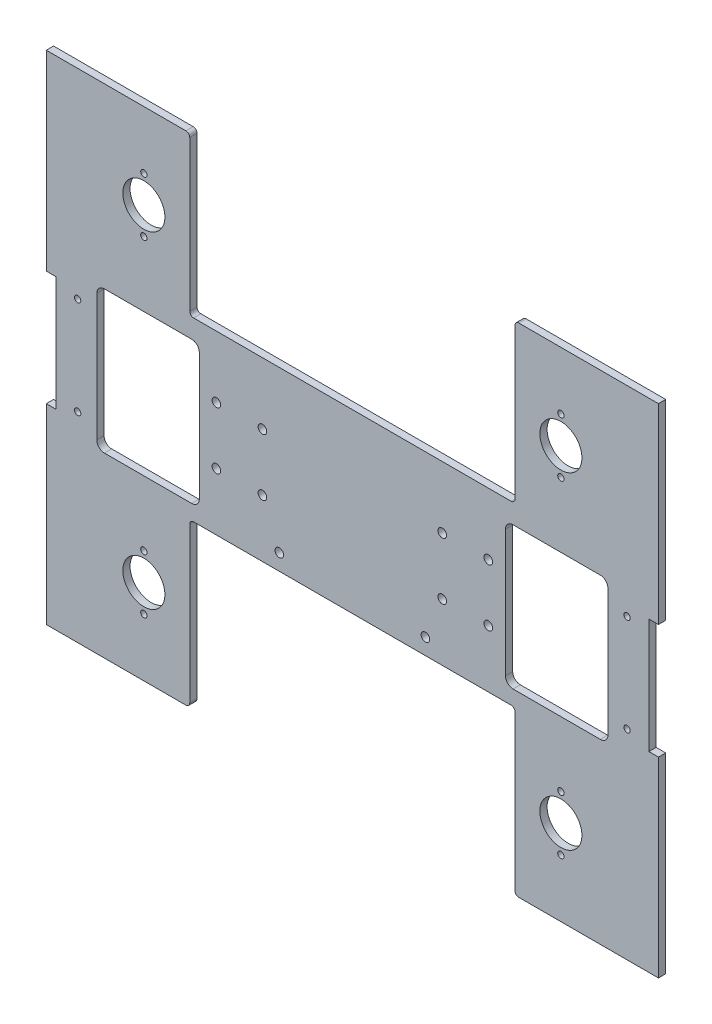
SolidWorks part; units mm, degrees
ref_plane "Front Plane" through (0, 0, 0) normal (0, 0, 1) x (1, 0, 0)
ref_plane "Top Plane" through (0, 0, 0) normal (0, 1, 0) x (1, 0, 0)
ref_plane "Right Plane" through (0, 0, 0) normal (1, 0, 0) x (0, 0, -1)
ref_plane "Plane1" through (0, 150, 0) normal (0, 1, 0) x (1, 0, 0)
ref_plane "Plane2" through (0, -150, 0) normal (0, 1, 0) x (1, 0, 0)
ref_plane "Plane3" through (150, 0, 0) normal (1, 0, 0) x (0, 0, -1)
ref_plane "Plane4" through (-150, 0, 0) normal (1, 0, 0) x (0, 0, -1)
sketch "Sketch2" plane through (0, 0, 0) normal (0, 0, 1) x (1, 0, 0)
  line L0 (0, -10.2) -> (0, 50.0764) construction
  line L5 (-71.06, 39.945) -> (-71.06, 10.055) construction
  line L23 (-160, 155) -> (-87, 155)
  line L24 (139.6652, 116) -> (168.3348, 116) construction
  line L31 (-160, -105) -> (-87, -105)
  line L40 (-152.1866, -81.0661) -> (-123.5266, -81.0661) construction
  line L42 (-85, 153) -> (-85, 74.3088)
  line L43 (-83, 72.3088) -> (83, 72.3088)
  line L47 (-84, 62.1714) -> (-129.5977, 62.1714)
  line L48 (84, 62.1714) -> (129.5977, 62.1714)
  line L49 (80, 58.1714) -> (80, -8.1714)
  line L50 (84, -12.1714) -> (129.5977, -12.1714)
  line L51 (133.5977, 58.1714) -> (133.5977, -8.1714)
  line L52 (80, 62.1714) -> (133.5977, -12.1714) construction
  line L53 (80, -12.1714) -> (133.5977, 62.1714) construction
  line L54 (-80, 58.1714) -> (-80, -8.1714)
  line L55 (-84, -12.1714) -> (-129.5977, -12.1714)
  line L56 (-133.5977, 58.1714) -> (-133.5977, -8.1714)
  line L57 (177.1787, -66.0847) -> (177.1787, 11.9153) construction
  line L70 (-143.5977, 50.5) -> (-143.5977, -0.5) construction
  line L73 (-160, 155) -> (-160, 55)
  line L74 (162.5, 25) -> (139.6652, 25) construction
  line L75 (-85, -103) -> (-85, -22)
  line L76 (-83, -20) -> (83, -20)
  line L79 (-160, -5) -> (-160, -105)
  line L80 (-160, -5) -> (-155, -5)
  line L82 (-160, 55) -> (-155, 55)
  line L83 (-155, -5) -> (-155, 55)
  line L84 (-145.4163, 25) -> (-155, 55) construction
  line L85 (-145.4163, 25) -> (-155, -5) construction
  line L88 (145.4163, 25) -> (155, -5) construction
  line L89 (145.4163, 25) -> (155, 55) construction
  line L90 (143.5977, 50.5) -> (143.5977, -0.5) construction
  line L91 (155, -5) -> (155, 55)
  line L92 (160, 55) -> (155, 55)
  line L93 (160, -5) -> (155, -5)
  line L94 (160, -5) -> (160, -105)
  line L95 (160, 155) -> (160, 55)
  line L96 (85, -103) -> (85, -22)
  line L97 (160, -105) -> (87, -105)
  line L98 (160, 155) -> (87, 155)
  line L99 (85, 153) -> (85, 74.3088)
  circle A1 centre (-108.9928, 124.7709) radius 1.65
  circle A2 centre (-108.9928, 96.1013) radius 1.65
  circle A3 centre (108.9928, 124.7709) radius 1.65
  circle A4 centre (108.9928, 96.1013) radius 1.65
  circle A9 centre (108.9928, 110.4361) radius 11
  circle A10 centre (-108.9928, 110.4361) radius 11
  circle A17 centre (143.5977, -0.5) radius 1.65
  circle A18 centre (143.5977, 50.5) radius 1.65
  circle A19 centre (-143.5977, -0.5) radius 1.65
  circle A20 centre (-143.5977, 50.5) radius 1.65
  circle A27 centre (-47, 10.055) radius 2.25
  circle A32 centre (-47, 39.945) radius 2.25
  circle A33 centre (-71.06, 39.945) radius 2.25
  circle A34 centre (-71.06, 10.055) radius 2.25
  circle A35 centre (71.06, 10.055) radius 2.25
  circle A36 centre (47, 10.055) radius 2.25
  circle A37 centre (47, 39.945) radius 2.25
  circle A38 centre (71.06, 39.945) radius 2.25
  arc A47 (-85, 153) -> (-87, 155) centre (-87, 153) ccw
  arc A48 (80, -8.1714) -> (84, -12.1714) centre (84, -8.1714) ccw
  arc A49 (129.5977, -12.1714) -> (133.5977, -8.1714) centre (129.5977, -8.1714) ccw
  arc A50 (129.5977, 62.1714) -> (133.5977, 58.1714) centre (129.5977, 58.1714) cw
  arc A51 (84, 62.1714) -> (80, 58.1714) centre (84, 58.1714) ccw
  arc A52 (-129.5977, 62.1714) -> (-133.5977, 58.1714) centre (-129.5977, 58.1714) ccw
  arc A53 (-84, 62.1714) -> (-80, 58.1714) centre (-84, 58.1714) cw
  arc A54 (-80, -8.1714) -> (-84, -12.1714) centre (-84, -8.1714) cw
  arc A55 (-129.5977, -12.1714) -> (-133.5977, -8.1714) centre (-129.5977, -8.1714) cw
  circle A68 centre (108.9928, -74.7709) radius 1.65
  circle A69 centre (108.9928, -46.1013) radius 1.65
  circle A70 centre (108.9928, -60.4361) radius 11
  circle A71 centre (-108.9928, -60.4361) radius 11
  circle A72 centre (-108.9928, -46.1013) radius 1.65
  circle A73 centre (-108.9928, -74.7709) radius 1.65
  arc A76 (-85, -22) -> (-83, -20) centre (-83, -22) cw
  arc A77 (-85, -103) -> (-87, -105) centre (-87, -103) cw
  arc A79 (85, -22) -> (83, -20) centre (83, -22) ccw
  arc A80 (85, -103) -> (87, -105) centre (87, -103) ccw
  arc A81 (85, 153) -> (87, 155) centre (87, 153) cw
  circle A82 centre (38.1799, -11.5638) radius 2.25
  circle A83 centre (-38.1799, -11.5638) radius 2.25
  arc A84 (85, 74.3088) -> (83, 72.3088) centre (83, 74.3088) cw
  arc A85 (-85, 74.3088) -> (-83, 72.3088) centre (-83, 74.3088) ccw
  point P0 (0, 0)
  point P2 (0, 0)
  point P4 (0, 150)
  point P7 (-145.4163, 25)
  point P11 (-143.5977, 25)
  point P12 (106.7989, 25)
  point P23 (-71.06, 25)
  point P24 (0, -20)
  point P33 (-155, 25)
  point P82 (177.1787, -27.0847)
  point P111 (-133.5977, 25)
  point P112 (145.4163, 25)
  point P122 (0, 72.3088)
  point P132 (-80, 25)
  point P141 (85, 72.3088)
  point P144 (-85, 72.3088)
  point P145 (108.9928, -60.4361)
  dimension "D3" = 51
  dimension "D7" = 160
  dimension "D8" = 3.3
  dimension "D9" = 85
  dimension "D10" = 22
  dimension "D11" = 74.3428
  dimension "D12" = 2
  dimension "D13" = 53.5977
  dimension "D16" = 80
  dimension "D17" = 5
  dimension "D18" = 60
  dimension "D19" = 3.3
  dimension "D6" = 14.3348
  dimension "D20" = 14.3348
  dimension "D21" = 130
  dimension "D23" = 4.5
  dimension "D24" = 45
  dimension "D25" = 4.5
  dimension "D26" = 4.5
  dimension "D27" = 29.89
  dimension "D29" = 24.06
  dimension "D31" = 4
  dimension "D32" = 130
  dimension "D4" = 3.3
  dimension "D5" = 10
  dimension "D22" = 29.89
  dimension "D28" = 24.06
  dimension "D15" = 33
  dimension "D14" = 2
extrude "Boss-Extrude1" add sketch "Sketch2" along normal blind 3.8
